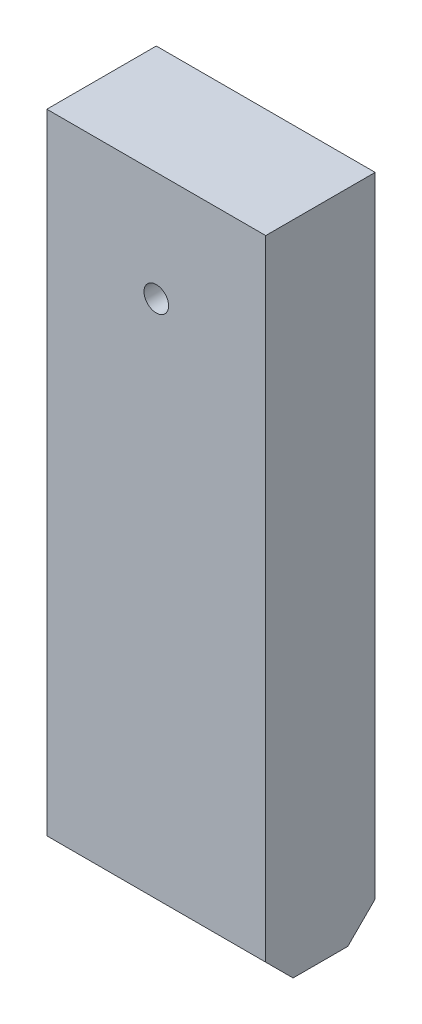
SolidWorks part; units mm, degrees
ref_plane "Plan de face" through (0, 0, 0) normal (0, 0, 1) x (1, 0, 0)
ref_plane "Plan de dessus" through (0, 0, 0) normal (0, 1, 0) x (1, 0, 0)
ref_plane "Plan de droite" through (0, 0, 0) normal (1, 0, 0) x (0, 0, -1)
sketch "Esquisse1" plane through (0, 0, 0) normal (0, 0, 1) x (1, 0, 0)
  line L1 (0, 0) -> (40, 0)
  line L2 (0, 0) -> (0, 120)
  line L3 (0, 120) -> (40, 120)
  line L4 (40, 0) -> (40, 120)
  dimension "D1" = 40
  dimension "D2" = 120
extrude "Boss.-Extru.1" add sketch "Esquisse1" along normal blind 20
chamfer "Chanfrein2" distance 5 angle 45 2 edges at (20, 0, 0) (20, 0, 20)
sketch "Esquisse3" plane through (0, 0, 20) normal (0, 0, 1) x (1, 0, 0)
  line L0 (20, 120) -> (20, 100) construction
  line L1 (40, 120) -> (0, 120) construction
  circle A0 centre (20, 100) radius 2.25
  dimension "D1" = 4.5
  dimension "D2" = 20
extrude "Enlèv. mat.-Extru.1" cut sketch "Esquisse3" against normal through all both and the other way through all
